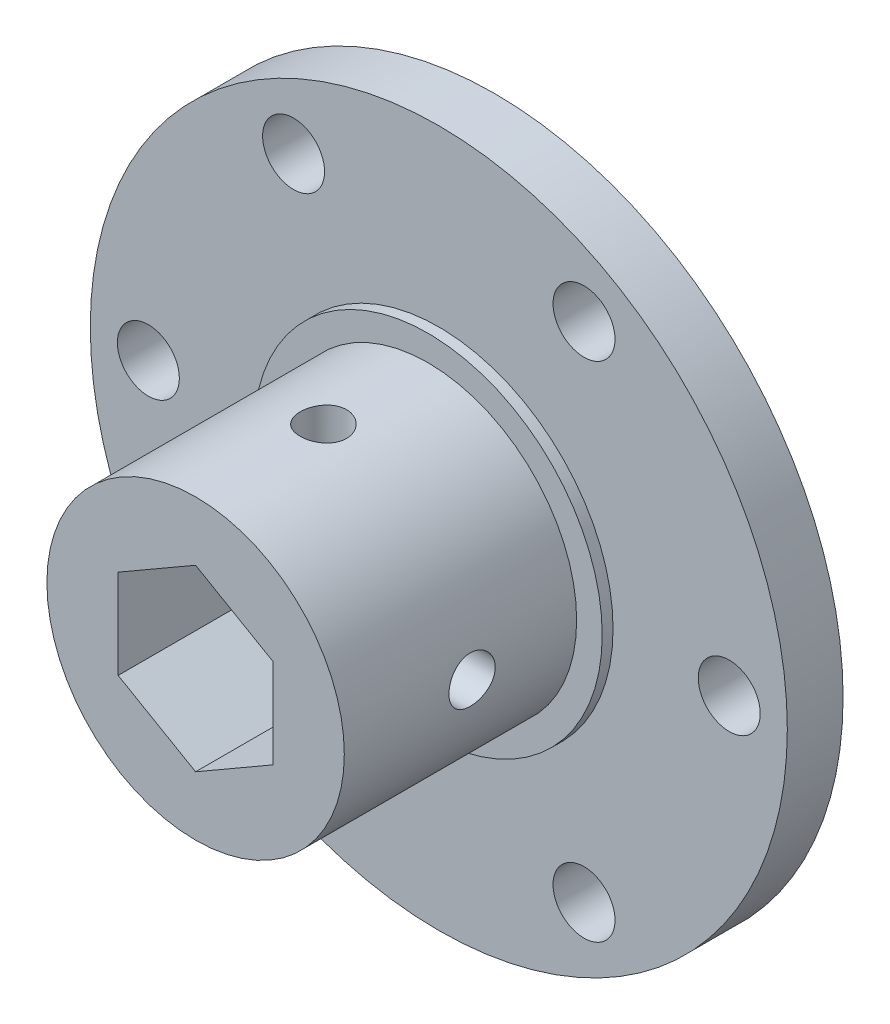
SolidWorks part; units mm, degrees
ref_plane "Front Plane" through (0, 0, 0) normal (0, 0, 1) x (1, 0, 0)
ref_plane "Top Plane" through (0, 0, 0) normal (0, 1, 0) x (1, 0, 0)
ref_plane "Right Plane" through (0, 0, 0) normal (1, 0, 0) x (0, 0, -1)
sketch "Sketch1" plane through (0, 0, 0) normal (0, 0, 1) x (1, 0, 0)
  circle A0 centre (0, 0) radius 14.2875
  dimension "D1" = 28.575
extrude "Boss-Extrude1" add sketch "Sketch1" along normal blind 0.889
sketch "Sketch2" plane through (0, 0, 0.889) normal (0, 0, 1) x (1, 0, 0)
  circle A0 centre (0, 0) radius 28.575
  dimension "D1" = 57.15
extrude "Boss-Extrude2" add sketch "Sketch2" along normal blind 4.572
sketch "Sketch3" plane through (0, 0, 5.461) normal (0, 0, 1) x (1, 0, 0)
  circle A0 centre (0, 0) radius 14.2875
  dimension "D1" = 28.575
extrude "Boss-Extrude3" add sketch "Sketch3" along normal blind 0.889
sketch "Sketch4" plane through (0, 0, 6.35) normal (0, 0, 1) x (1, 0, 0)
  circle A0 centre (0, 0) radius 12.192
  dimension "D1" = 24.384
extrude "Boss-Extrude4" add sketch "Sketch4" along normal blind 19.05
sketch "Sketch5" plane through (0, 0, 0.889) normal (0, 0, -1) x (-1, 0, 0)
  line L0 (0, 0) -> (0, 23.8125)
  line L1 (0, 23.8125) -> (0, 0)
  line L2 (0, 0) -> (-11.9063, 20.6222)
  circle A0 centre (0, 0) radius 23.8125
  circle A1 centre (-11.9063, 20.6222) radius 2.54
  circle A2 centre (0, 0) radius 23.8125
  circle A3 centre (11.9063, 20.6222) radius 2.54
  circle A4 centre (0, 0) radius 23.8125
  circle A5 centre (23.8125, 0) radius 2.54
  circle A6 centre (0, 0) radius 23.8125
  circle A7 centre (11.9063, -20.6222) radius 2.54
  circle A8 centre (0, 0) radius 23.8125
  circle A9 centre (-11.9063, -20.6222) radius 2.54
  circle A10 centre (0, 0) radius 23.8125
  circle A11 centre (-23.8125, 0) radius 2.54
  point P23 (0, 0)
  dimension "D2" = 5.08
  dimension "D3" = 47.625
  dimension "D1" = 30
  dimension "D4" = 6
extrude "Cut-Extrude1" cut sketch "Sketch5" against normal through all contours A1 | A11 | A9 | A7 | A5 | A3
sketch "Sketch6" plane through (0, 0, 25.4) normal (0, 0, 1) x (1, 0, 0)
  line L0 (0, 0) -> (0, 7.3323)
  line L1 (0, 7.3323) -> (-6.35, 3.6662)
  line L2 (-6.35, 3.6662) -> (-6.35, -3.6662)
  line L3 (-6.35, -3.6662) -> (0, -7.3323)
  line L4 (0, -7.3323) -> (6.35, -3.6662)
  line L5 (6.35, -3.6662) -> (6.35, 3.6662)
  line L6 (6.35, 3.6662) -> (0, 7.3323)
  circle A0 centre (0, 0) radius 6.35 construction
  dimension "D1" = 12.7
extrude "Cut-Extrude2" cut sketch "Sketch6" against normal through all
hole_wizard "#10-24 Tapped Hole1" positions "3DSketch1" profile "Sketch7" tap size "#10-24" standard "ANSI Inch" end condition through all
sketch3d "3DSketch1"
  point P0 (12.192, 0, 14.9225)
  dimension "D1" = 8.5725
sketch "Sketch7" plane through (12.192, 0, 14.9225) normal (0, 1, 0) x (0, 0, -1)
  line L0 (0, 0) -> (0, 40.767)
  line L1 (0, 40.767) -> (1.8986, 40.767)
  line L2 (1.8986, 40.767) -> (1.8986, 0)
  line L5 (1.8986, 0) -> (0, 0)
  line L11 (0, -6.35) -> (0, 107.95) construction
  dimension "Thru Tap Drill Dia." = 3.7973
  dimension "Thru Tap Drill Depth" = 40.767
cosmetic thread "Hole Thread2" parameters "D2"=4.826
pattern_circular "CirPattern1" count 2 every 90 about axis through (0, 0, 5.461) along (0, 0, 1) of "#10-24 Tapped Hole1"
